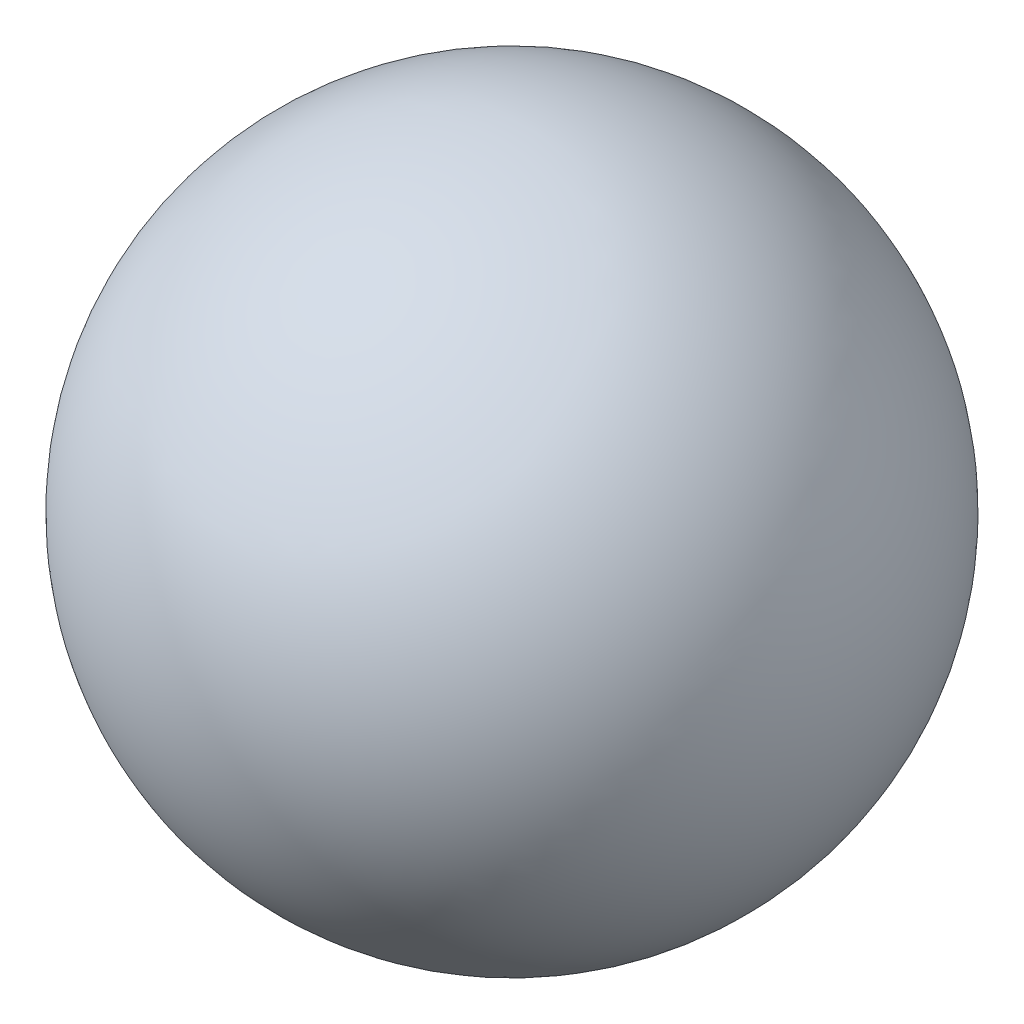
SolidWorks part; units mm, degrees
ref_plane "前视基准面" through (0, 0, 0) normal (0, 0, 1) x (1, 0, 0)
ref_plane "上视基准面" through (0, 0, 0) normal (0, 1, 0) x (1, 0, 0)
ref_plane "右视基准面" through (0, 0, 0) normal (1, 0, 0) x (0, 0, -1)
sketch "草图1" plane through (0, 0, 0) normal (0, 1, 0) x (1, 0, 0)
  line L0 (0, 8.5) -> (0, -8.5) construction
  line L1 (0, 8.5) -> (0, -8.5)
  arc A0 (0, 8.5) -> (0, -8.5) centre (0, 0) ccw
  point P4 (0, 0)
  dimension "D1" = 17
revolve "旋转1" add sketch "草图1" angle 360 about L0
equation "\"m\"= 2"
